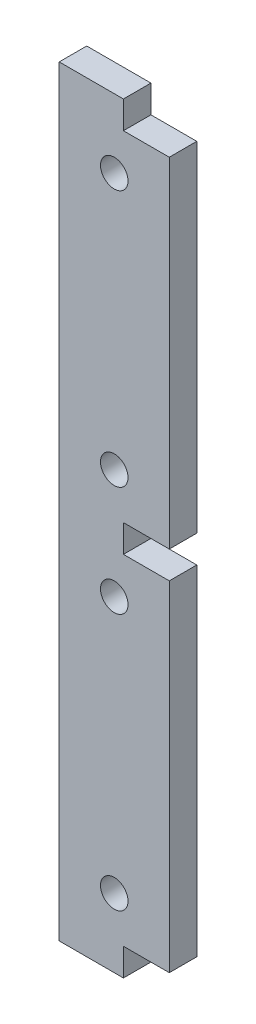
SolidWorks part; units mm, degrees
ref_plane "Plan de face" through (0, 0, 0) normal (0, 0, 1) x (1, 0, 0)
ref_plane "Plan de dessus" through (0, 0, 0) normal (0, 1, 0) x (1, 0, 0)
ref_plane "Plan de droite" through (0, 0, 0) normal (1, 0, 0) x (0, 0, -1)
sketch "Esquisse1" plane through (0, 0, 0) normal (0, 0, 1) x (1, 0, 0)
  line L0 (-6, 0) -> (6, 0)
  line L1 (6, 0) -> (6, 118) construction
  line L2 (6, 118) -> (-6, 118)
  line L3 (-6, 118) -> (-6, 0)
  line L4 (0, 118) -> (0, 0) construction
  line L10 (6, 100.5) -> (1, 100.5)
  line L11 (1, 100.5) -> (1, 97.5)
  line L12 (1, 97.5) -> (6, 97.5)
  line L13 (6, 97.5) -> (6, 60.5)
  line L14 (6, 60.5) -> (1, 60.5)
  line L15 (1, 60.5) -> (1, 57.5)
  line L16 (1, 57.5) -> (6, 57.5)
  line L17 (6, 57.5) -> (6, 20.5)
  line L18 (6, 20.5) -> (1, 20.5)
  line L19 (1, 20.5) -> (1, 17.5)
  line L20 (1, 17.5) -> (6, 17.5)
  line L25 (6, 17.5) -> (6, 0)
  line L26 (1, 99) -> (6, 99) construction
  line L27 (1, 59) -> (6, 59) construction
  line L28 (1, 19) -> (6, 19) construction
  line L32 (3.5, 298) -> (3.5, 99) construction
  line L33 (3.5, 99) -> (3.5, 59) construction
  line L34 (3.5, 59) -> (3.5, 19) construction
  line L35 (3.5, 19) -> (3.5, -180) construction
  line L36 (3.5, 298) -> (3.5, 118) construction
  line L38 (6, 118) -> (6, 100.5)
  point P46 (-0.4418, 19)
  circle B0 centre (0, 105) radius 1.5
  circle B1 centre (0, 93) radius 1.5
  line B2 (-9.0699, 99) -> (8.1862, 99) construction
  circle B3 centre (0, 65) radius 1.5
  circle B4 centre (0, 53) radius 1.5
  line B5 (-9.0699, 59) -> (8.1862, 59) construction
  circle B6 centre (0, 25) radius 1.5
  circle B7 centre (0, 13) radius 1.5
  line B8 (-9.0699, 19) -> (8.1862, 19) construction
  dimension "D1" = 40
  dimension "D2" = 17.5
  dimension "D3" = 3
  dimension "D4" = 12
  dimension "D5" = 5
sketch_block_instance "Bloc1-2"
sketch_block "Bloc1" parameters "D1"=3, "D3"=3, "D2"=12
sketch_block_instance "Bloc1-3"
sketch_block_instance "Bloc1-5"
extrude "Boss.-Extru.1" add sketch "Esquisse1" along normal blind 3
sketch "Esquisse2" plane through (0, 0, 3) normal (0, 0, 1) x (1, 0, 0)
  line L1 (-6, 118) -> (6, 118)
  line L2 (-6, 118) -> (-6, 100.5)
  line L3 (-6, 100.5) -> (6, 100.5)
  line L4 (6, 118) -> (6, 100.5)
  line L5 (-6, 0) -> (6, 0)
  line L6 (-6, 0) -> (-6, 17.5)
  line L7 (-6, 17.5) -> (6, 17.5)
  line L8 (6, 0) -> (6, 17.5)
extrude "Enlèv. mat.-Extru.1" cut sketch "Esquisse2" against normal through all
